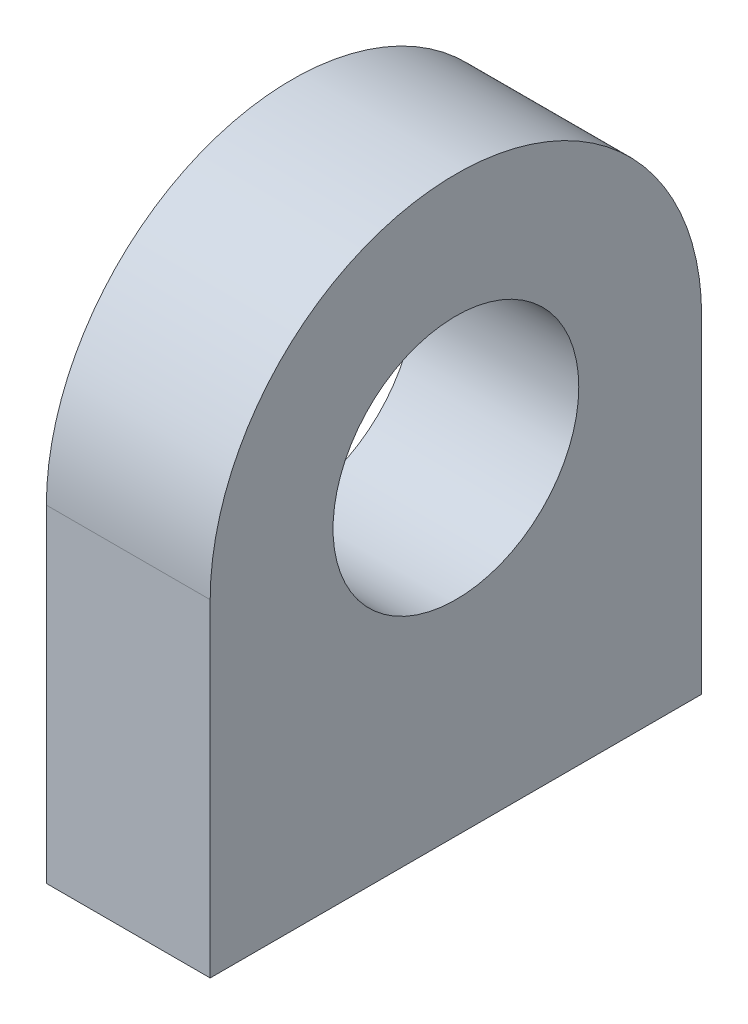
SolidWorks part; units mm, degrees
ref_plane "Front Plane" through (0, 0, 0) normal (0, 0, 1) x (1, 0, 0)
ref_plane "Top Plane" through (0, 0, 0) normal (0, 1, 0) x (1, 0, 0)
ref_plane "Right Plane" through (0, 0, 0) normal (1, 0, 0) x (0, 0, -1)
sketch "Sketch1" plane through (0, 0, 0) normal (1, 0, 0) x (0, 0, -1)
  line L0 (-15, -20) -> (15, -20)
  line L1 (-15, 0) -> (-15, -20)
  line L2 (15, 0) -> (15, -20)
  circle A0 centre (0, 0) radius 7.5
  arc A1 (15, 0) -> (-15, 0) centre (0, 0) ccw
  dimension "D1" = 15
  dimension "D2" = 30
  dimension "D3" = 20
extrude "Boss-Extrude1" add sketch "Sketch1" along normal blind 10
